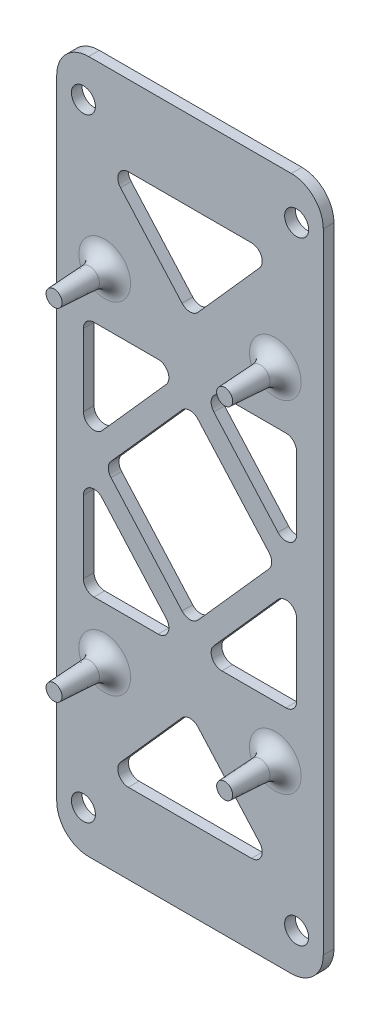
SolidWorks part; units mm, degrees
ref_plane "前视基准面" through (0, 0, 0) normal (0, 0, 1) x (1, 0, 0)
ref_plane "上视基准面" through (0, 0, 0) normal (0, 1, 0) x (1, 0, 0)
ref_plane "右视基准面" through (0, 0, 0) normal (1, 0, 0) x (0, 0, -1)
other "Configuration Table"
sketch "草图1" plane through (0, 0, 0) normal (0, 0, 1) x (1, 0, 0)
  line L0 (0, -65) -> (50, -65) construction
  line L1 (0, 0) -> (50, 0)
  line L2 (0, 0) -> (0, -130)
  line L3 (0, -130) -> (50, -130)
  line L4 (50, 0) -> (50, -130)
  line L5 (25, 0) -> (25, -130) construction
  line L6 (0, -7.5) -> (50, -7.5) construction
  line L7 (0, -122.5) -> (50, -122.5)
  circle A0 centre (5, -7.5) radius 2.25
  circle A1 centre (45, -7.5) radius 2.25
  circle A2 centre (45, -122.5) radius 2.25
  circle A3 centre (5, -122.5) radius 2.25
  dimension "D4" = 40
  dimension "D5" = 4.5
  dimension "D1" = 130
  dimension "D2" = 50
  dimension "D3" = 7.5
extrude "凸台-拉伸1" add sketch "草图1" along normal blind 2 contours L7 A3 A2 L4 L1 L2 A1 A0 | L7 A3 L2 L3 L4 A2
fillet "圆角1" radius 6 4 edges at (50, 0, 1) (50, -130, 1) (0, -130, 1) (0, 0, 1)
sketch "草图2" plane through (0, 0, 2) normal (0, 0, 1) x (1, 0, 0)
  line L3 (0, -65) -> (50, -65) construction
  line L4 (50, 0) -> (0, 0)
  line L5 (50, -130) -> (50, 0)
  line L6 (0, -130) -> (50, -130)
  line L7 (0, 0) -> (0, -130)
  line L8 (50, 0) -> (0, 0)
  line L9 (50, -130) -> (50, 0)
  line L10 (0, -130) -> (50, -130)
  line L11 (0, 0) -> (0, -130)
  line L12 (25, 0) -> (25, -130) construction
  circle A0 centre (9, -33) radius 1.75
  circle A1 centre (5, -7.5) radius 2.25
  circle A2 centre (5, -7.5) radius 2.25
  circle A3 centre (5, -122.5) radius 2.25
  circle A4 centre (5, -122.5) radius 2.25
  circle A5 centre (45, -122.5) radius 2.25
  circle A6 centre (45, -122.5) radius 2.25
  circle A7 centre (45, -7.5) radius 2.25
  circle A8 centre (45, -7.5) radius 2.25
  circle A9 centre (41, -33) radius 1.75
  circle A10 centre (9, -97) radius 1.75
  circle A11 centre (41, -97) radius 1.75
  dimension "D6" = 32
  dimension "D8" = 3.5
  dimension "D7" = 64
  dimension "D1" = 0
  dimension "D2" = 0
  dimension "D3" = 0
  dimension "D4" = 0
  dimension "D5" = 0
ref_plane "基准面2" through (0, -33, 0) normal (0, 1, 0) x (1, 0, 0)
sketch "草图5" plane through (0, -33, 0) normal (0, 1, 0) x (1, 0, 0)
  line L0 (41, -2) -> (41, -11.5)
  line L1 (41, -2) -> (43, -2)
  line L2 (39.25, -2) -> (42.75, -2) construction
  line L3 (41, -11.5) -> (42.5, -11.5)
  line L4 (43, -2) -> (42.5, -11.5)
  line L5 (25, -2) -> (25, 0) construction
  line L6 (50, -2) -> (0, -2) construction
  line L7 (6, 0) -> (44, 0) construction
  line L8 (9, -2) -> (7, -2)
  line L9 (9, -2) -> (9, -11.5)
  line L10 (9, -11.5) -> (7.5, -11.5)
  line L11 (7, -2) -> (7.5, -11.5)
  dimension "D1" = 9.5
  dimension "D2" = 2
  dimension "D3" = 1.5
revolve "旋转1" add sketch "草图5" angle 360 about L9
ref_plane "基准面3" through (0, -65, 0) normal (0, 1, 0) x (1, 0, 0)
ref_plane "基准面4" through (25, 0, 0) normal (-1, 0, 0) x (0, 0, 1)
mirror "镜向1" about plane through (25, 0, 0) normal (-1, 0, 0) of "旋转1" second plane through (0, -65, 0) second plane normal (0, 1, 0)
fillet "圆角2" radius 3 4 edges at (11, -33, 2) (11, -97, 2) (43, -33, 2) (43, -97, 2)
sketch "草图6" plane through (0, 0, 2) normal (0, 0, 1) x (1, 0, 0)
  line L0 (9, -33) -> (41, -33)
  line L4 (50, -124) -> (50, -6)
  line L5 (44, 0) -> (6, 0)
  line L6 (0, -6) -> (0, -124)
  line L7 (6, -130) -> (44, -130)
  line L8 (50, -124) -> (50, -6)
  line L9 (44, 0) -> (6, 0)
  line L10 (0, -6) -> (0, -124)
  line L11 (6, -130) -> (44, -130)
  arc A4 (50, -6) -> (44, 0) centre (44, -6) ccw
  arc A5 (6, 0) -> (0, -6) centre (6, -6) ccw
  arc A6 (0, -124) -> (6, -130) centre (6, -124) ccw
  arc A7 (44, -130) -> (50, -124) centre (44, -124) ccw
  arc A8 (50, -6) -> (44, 0) centre (44, -6) ccw
  arc A9 (6, 0) -> (0, -6) centre (6, -6) ccw
  arc A10 (0, -124) -> (6, -130) centre (6, -124) ccw
  arc A11 (44, -130) -> (50, -124) centre (44, -124) ccw
  dimension "D1" = 0
sketch "草图7" plane through (0, 0, 2) normal (0, 0, 1) x (1, 0, 0)
  line L0 (0, -15) -> (50, -15)
  line L1 (0, 0) -> (0, -130) construction
  line L2 (50, -130) -> (50, 0) construction
  line L3 (50, 0) -> (0, 0) construction
  line L4 (9, -15) -> (25, -33)
  line L5 (9, -33) -> (41, -33) construction
  line L6 (25, -33) -> (41, -15)
  line L7 (25, 0) -> (25, -130) construction
  line L8 (25, 0) -> (25, -130) construction
  line L9 (0, -65) -> (50, -65) construction
  line L10 (9, -65) -> (25, -47)
  line L11 (25, -47) -> (41, -65)
  line L12 (0, -115) -> (50, -115)
  line L13 (9, -115) -> (25, -97)
  line L14 (25, -97) -> (41, -115)
  line L15 (9, -65) -> (25, -83)
  line L16 (25, -83) -> (41, -65)
  dimension "D1" = 15
  dimension "D2" = 32
  dimension "D3" = 32
  dimension "D4" = 18
extrude "切除-拉伸1" cut sketch "草图7" against normal blind 2 contours L4 L6 L0 | L15 L16 L11 L10 | L14 L13 L12
fillet "圆角3" radius 2 10 edges at (9, -115, 1) (41, -115, 1) (25, -97, 1) (25, -83, 1) (41, -65, 1) (9, -65, 1) (25, -47, 1) (25, -33, 1) (41, -15, 1) (9, -15, 1)
sketch "草图8" plane through (0, 0, 2) normal (0, 0, 1) x (1, 0, 0)
  line L0 (0, -65) -> (50, -65) construction
  line L1 (0, -65) -> (50, -65) construction
  line L2 (26.4948, -48.6817) -> (39.8189, -63.6713) construction
  line L3 (26.4948, -81.3183) -> (39.8189, -66.3287) construction
  line L4 (10.1811, -66.3287) -> (23.5052, -81.3183) construction
  line L5 (10.1811, -63.6713) -> (23.5052, -48.6817) construction
  line L6 (26.4948, -48.6817) -> (39.8189, -63.6713)
  line L7 (26.4948, -81.3183) -> (39.8189, -66.3287)
  line L8 (10.1811, -66.3287) -> (23.5052, -81.3183)
  line L9 (10.1811, -63.6713) -> (23.5052, -48.6817)
  line L10 (26.5133, -42.6817) -> (45, -42.6817)
  line L11 (45, -42.6817) -> (45, -63.4792)
  line L12 (45, -63.4792) -> (26.5133, -42.6817)
  line L13 (50, -130) -> (50, 0) construction
  line L14 (25, 0) -> (25, -130) construction
  line L15 (25, 0) -> (25, -130) construction
  line L16 (5, -42.6817) -> (5, -63.4792)
  line L17 (23.4867, -42.6817) -> (5, -42.6817)
  line L18 (5, -63.4792) -> (23.4867, -42.6817)
  line L19 (45, -87.3183) -> (45, -66.5208)
  line L20 (26.5133, -87.3183) -> (45, -87.3183)
  line L21 (45, -66.5208) -> (26.5133, -87.3183)
  line L22 (23.4867, -87.3183) -> (5, -87.3183)
  line L23 (5, -66.5208) -> (23.4867, -87.3183)
  line L24 (5, -87.3183) -> (5, -66.5208)
  dimension "D1" = 4
  dimension "D2" = 5
  dimension "D3" = 6
extrude "切除-拉伸2" cut sketch "草图8" against normal blind 2 contours L16 L18 L17 | L12 L11 L10 | L19 L21 L20 | L24 L22 L23
fillet "圆角4" radius 2 12 edges at (23.4867, -87.3183, 1) (5, -66.5208, 1) (5, -87.3183, 1) (45, -87.3183, 1) (26.5133, -87.3183, 1) (45, -66.5208, 1) (45, -63.4792, 1) (26.5133, -42.6817, 1) (45, -42.6817, 1) (5, -63.4792, 1) (23.4867, -42.6817, 1) (5, -42.6817, 1)
